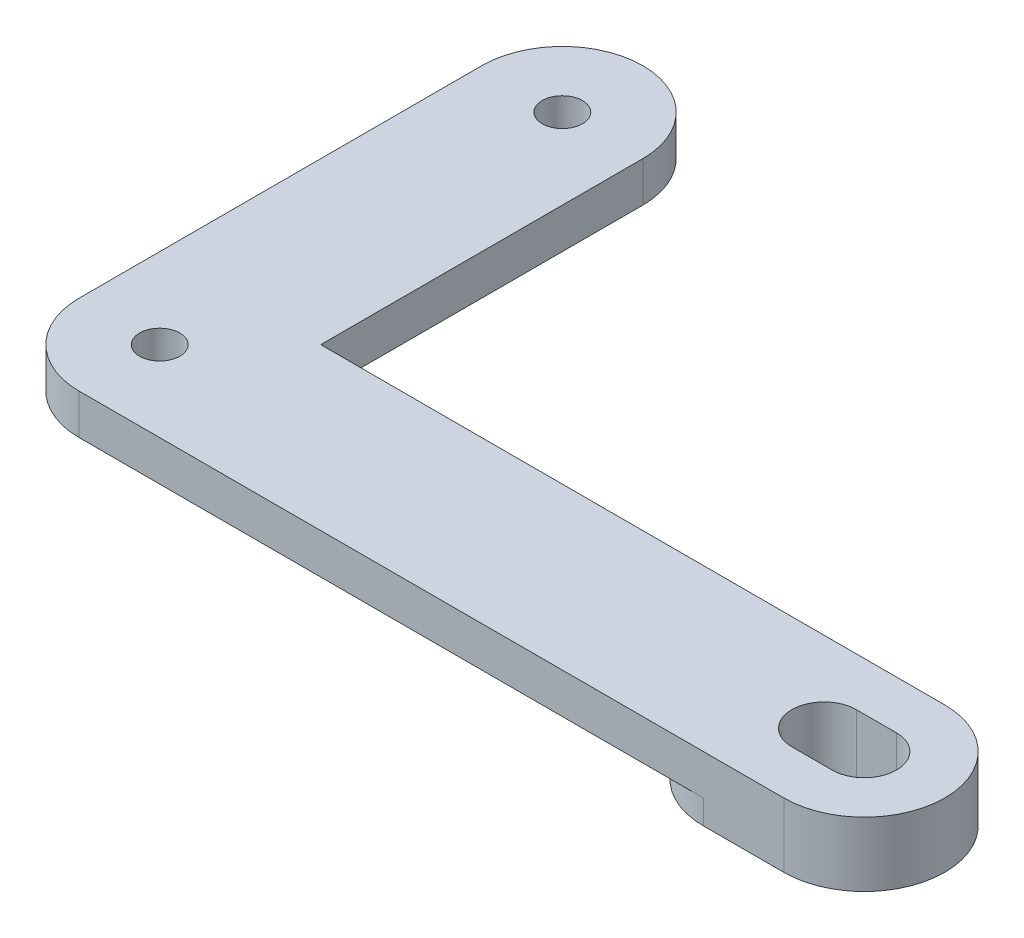
SolidWorks part; units mm, degrees
ref_plane "Front Plane" through (0, 0, 0) normal (0, 0, 1) x (1, 0, 0)
ref_plane "Top Plane" through (0, 0, 0) normal (0, 1, 0) x (1, 0, 0)
ref_plane "Right Plane" through (0, 0, 0) normal (1, 0, 0) x (0, 0, -1)
sketch "Sketch1" plane through (0, 0, 0) normal (0, 1, 0) x (1, 0, 0)
  line L0 (0, 0) -> (87.5, 0) construction
  line L1 (0, 10) -> (87.5, 10)
  line L2 (0, -10) -> (87.5, -10)
  line L3 (87.5, 0) -> (82.5, 0) construction
  line L4 (87.5, -4) -> (82.5, -4)
  line L5 (87.5, 4) -> (82.5, 4)
  arc A0 (0, 10) -> (0, -10) centre (0, 0) ccw
  arc A1 (87.5, -10) -> (87.5, 10) centre (87.5, 0) ccw
  arc A2 (87.5, -4) -> (87.5, 4) centre (87.5, 0) ccw
  circle A3 centre (0, 0) radius 2.5
  arc A4 (82.5, 4) -> (82.5, -4) centre (82.5, 0) ccw
  point P3 (43.75, 0)
  point P12 (85, 0)
  dimension "D1" = 4
  dimension "D2" = 10
  dimension "D4" = 5
  dimension "D5" = 5
  dimension "D3" = 85
extrude "Boss-Extrude1" add sketch "Sketch1" along normal blind 8
sketch "Sketch2" plane through (0, 8, 0) normal (0, 1, 0) x (1, 0, 0)
  line L0 (0, 0) -> (0, 50) construction
  line L1 (-10, 0) -> (-10, 50)
  line L2 (10, 0) -> (10, 50)
  arc A0 (-10, 0) -> (10, 0) centre (0, 0) ccw
  arc A1 (10, 50) -> (-10, 50) centre (0, 50) ccw
  arc A2 (0, 10) -> (0, -10) centre (0, 0) ccw construction
  circle A3 centre (0, 0) radius 2.5
  circle A4 centre (0, 0) radius 2.5 construction
  circle A5 centre (0, 50) radius 2.5
  point P3 (0, 25)
  dimension "D2" = 5
  dimension "D1" = 50
extrude "Boss-Extrude2" add sketch "Sketch2" against normal blind 5
sketch "Sketch3" plane through (0, 0, 0) normal (0, -1, 0) x (1, 0, 0)
  line L0 (87.5, 0) -> (77.5, 0) construction
  line L1 (87.5, -10) -> (77.5, -10)
  line L2 (87.5, 10) -> (77.5, 10)
  arc A0 (87.5, -10) -> (87.5, 10) centre (87.5, 0) ccw
  arc A1 (77.5, 10) -> (77.5, -10) centre (77.5, 0) ccw
  arc A2 (87.5, -10) -> (87.5, 10) centre (87.5, 0) ccw construction
  point P3 (82.5, 0)
  dimension "D1" = 10
extrude "Cut-Extrude2" cut sketch "Sketch3" against normal up to surface (3 mm away) flip side to cut up to face at (0, 3, -47.5)
